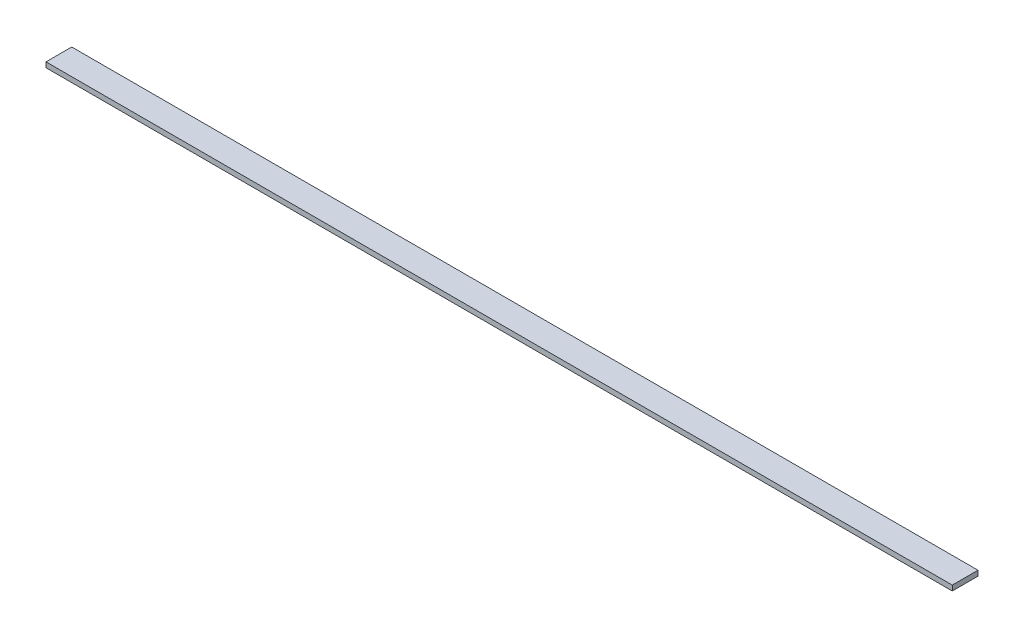
SolidWorks part; units mm, degrees
ref_plane "前视基准面" through (0, 0, 0) normal (0, 0, 1) x (1, 0, 0)
ref_plane "上视基准面" through (0, 0, 0) normal (0, 1, 0) x (1, 0, 0)
ref_plane "右视基准面" through (0, 0, 0) normal (1, 0, 0) x (0, 0, -1)
sketch "草图1" plane through (0, 0, 0) normal (0, 1, 0) x (1, 0, 0)
  line L1 (-65.2785, 23.106) -> (286.9315, 23.106)
  line L2 (-65.2785, 23.106) -> (-65.2785, 13.106)
  line L3 (-65.2785, 13.106) -> (286.9315, 13.106)
  line L4 (286.9315, 23.106) -> (286.9315, 13.106)
  dimension "D1" = 352.21
  dimension "D2" = 10
extrude "凸台-拉伸1" add sketch "草图1" along normal blind 2
